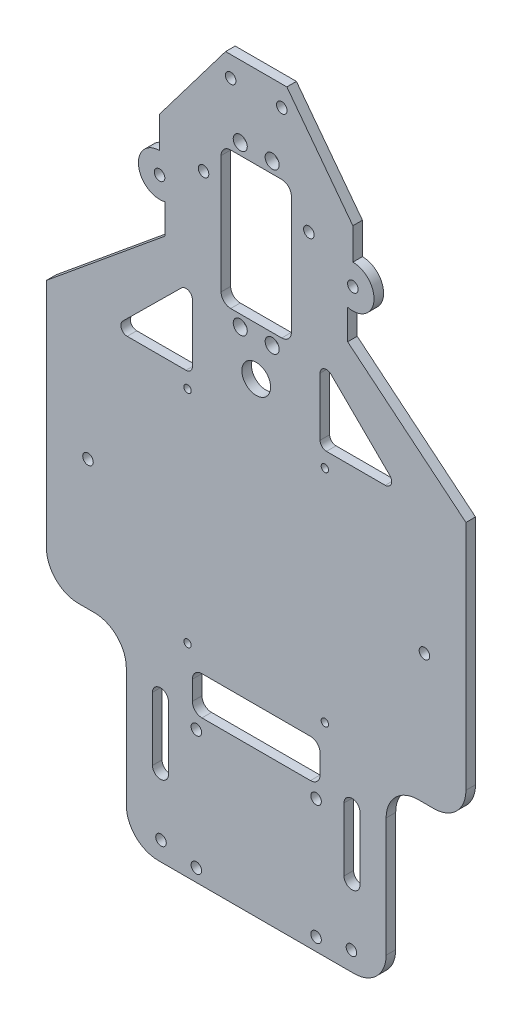
SolidWorks part; units mm, degrees
ref_plane "Front Plane" through (0, 0, 0) normal (0, 0, 1) x (1, 0, 0)
ref_plane "Top Plane" through (0, 0, 0) normal (0, 1, 0) x (1, 0, 0)
ref_plane "Right Plane" through (0, 0, 0) normal (1, 0, 0) x (0, 0, -1)
sketch "Sketch1" plane through (0, 0, 0) normal (0, 0, 1) x (1, 0, 0)
  line L0 (0, 88.6559) -> (0, -280.1214) construction
  line L6 (-65.69, -25.0893) -> (-65.69, -107.7412)
  line L7 (-65.69, -107.7412) -> (-40.69, -107.7412)
  line L8 (-40.69, -107.7412) -> (-40.69, -164.9822)
  line L9 (-40.69, -164.9822) -> (40.69, -164.9822)
  line L14 (65.69, -25.0893) -> (65.69, -107.7412)
  line L15 (65.69, -107.7412) -> (40.69, -107.7412)
  line L16 (40.69, -107.7412) -> (40.69, -164.9822)
  line L17 (-29.8217, -153.2205) -> (-29.8217, -163.4841) construction
  line L18 (-37.8742, -161.3701) -> (-20.3793, -161.3701) construction
  line L19 (-52.6928, -38.7906) -> (-52.6928, -94.6639) construction
  line L20 (-83.9092, -67.0943) -> (-28.9526, -67.0943) construction
  line L21 (52.6928, -38.7906) -> (52.6928, -94.6639) construction
  line L22 (83.9092, -67.0943) -> (28.9526, -67.0943) construction
  line L23 (37.8742, -161.3701) -> (20.3793, -161.3701) construction
  line L24 (29.8217, -153.2205) -> (29.8217, -163.4841) construction
  line L27 (-65.69, -25.0893) -> (-28.6418, 5.3966)
  line L28 (-30, -120.271) -> (-30, -140.086) construction
  line L29 (-11, 39.1077) -> (11, 39.1077)
  line L30 (-11, 39.1077) -> (-11, -3.8923)
  line L31 (-11, -3.8923) -> (11, -3.8923)
  line L32 (11, 39.1077) -> (11, -3.8923)
  line L33 (-11, 39.1077) -> (11, -3.8923) construction
  line L34 (-11, -3.8923) -> (11, 39.1077) construction
  line L35 (-20, -104.4501) -> (20, -104.4501)
  line L36 (-20, -104.4501) -> (-20, -116.4501)
  line L37 (-20, -116.4501) -> (20, -116.4501)
  line L38 (20, -104.4501) -> (20, -116.4501)
  line L39 (-20, -104.4501) -> (20, -116.4501) construction
  line L40 (-20, -116.4501) -> (20, -104.4501) construction
  line L43 (-27.5, -120.271) -> (-27.5, -140.086)
  line L44 (-32.5, -120.271) -> (-32.5, -140.086)
  line L45 (30, -120.271) -> (30, -140.086) construction
  line L46 (27.5, -120.271) -> (27.5, -140.086)
  line L47 (32.5, -120.271) -> (32.5, -140.086)
  line L48 (20, -2.6427) -> (20, -27.6411)
  line L49 (20, -27.6411) -> (45.282, -27.6411)
  line L50 (45.282, -27.6411) -> (20, -2.6427)
  line L51 (-20, -27.6411) -> (-45.282, -27.6411)
  line L52 (-20, -2.6427) -> (-20, -27.6411)
  line L53 (-45.282, -27.6411) -> (-20, -2.6427)
  line L54 (-28.6418, 5.3966) -> (-28.6418, 14.7716)
  line L55 (-30.2776, 27.8213) -> (-30.2776, 37.6956)
  line L56 (-30.2776, 37.6956) -> (-9.5976, 65.0178)
  line L57 (-9.5976, 65.0178) -> (9.5976, 65.0178)
  line L58 (65.69, -25.0893) -> (28.6418, 5.3966)
  line L59 (28.6418, 5.3966) -> (28.6418, 14.7716)
  line L60 (30.2776, 27.8213) -> (30.2776, 37.6956)
  line L61 (30.2776, 37.6956) -> (9.5976, 65.0178)
  line L62 (-5.5214, -18.9822) -> (5.7974, -18.9822) construction
  line L63 (-49.4927, 29.1077) -> (49.3693, 29.1077) construction
  line L64 (-16.5, 40.8846) -> (-16.5, 28.6939) construction
  line L65 (16.5, 40.8846) -> (16.5, 28.6939) construction
  line L66 (-43.1126, 58.6077) -> (47.2987, 58.6077) construction
  line L67 (-8, 55.9424) -> (-8, 45.929) construction
  line L68 (8, 55.9424) -> (8, 45.929) construction
  line L69 (-40.69, 17.6077) -> (39.8694, 17.6077) construction
  line L70 (-11.4384, 42.6077) -> (11.9873, 42.6077) construction
  line L71 (5, 45.2623) -> (5, 40.4022) construction
  line L72 (-5, 45.2623) -> (-5, 40.4022) construction
  line L73 (-11.4384, -7.3923) -> (11.9873, -7.3923) construction
  line L74 (-5, -10.0468) -> (-5, -5.1867) construction
  line L75 (5, -10.0468) -> (5, -5.1867) construction
  line L76 (-36.2555, -160.9822) -> (34.7157, -160.9822) construction
  line L77 (-23.9765, -142.2322) -> (17.7395, -142.2322) construction
  line L78 (-18.75, -157.7593) -> (-18.75, -163.4841) construction
  line L79 (18.75, -157.7593) -> (18.75, -163.4841) construction
  line L80 (-36.2555, -123.4822) -> (34.7157, -123.4822) construction
  line L81 (18.75, -126.7051) -> (18.75, -120.9804) construction
  line L82 (-18.75, -126.7051) -> (-18.75, -120.9804) construction
  line L83 (-87.3317, -66.9501) -> (108.5415, -66.9501) construction
  line L84 (13.0043, -101.4501) -> (41.7879, -101.4501) construction
  line L85 (21.5, -89.8072) -> (21.5, -113.3293) construction
  line L86 (-13.0043, -101.4501) -> (-41.7879, -101.4501) construction
  line L87 (-21.5, -89.8072) -> (-21.5, -113.3293) construction
  line L88 (13.0043, -32.4501) -> (41.7879, -32.4501) construction
  line L89 (21.5, -44.0929) -> (21.5, -20.5709) construction
  line L90 (-13.0043, -32.4501) -> (-41.7879, -32.4501) construction
  line L91 (-21.5, -44.0929) -> (-21.5, -20.5709) construction
  circle A2 centre (-30.2776, 21.1939) radius 1.65
  circle A3 centre (-29.8217, -158.9822) radius 1.65
  circle A5 centre (-52.6928, -67.0943) radius 1.65
  circle A6 centre (30.2776, 21.1939) radius 1.65
  circle A7 centre (52.6928, -67.0943) radius 1.65
  circle A8 centre (29.8217, -158.9822) radius 1.65
  arc A13 (-27.5, -120.271) -> (-32.5, -120.271) centre (-30, -120.271) ccw
  arc A14 (-32.5, -140.086) -> (-27.5, -140.086) centre (-30, -140.086) ccw
  arc A15 (27.5, -120.271) -> (32.5, -120.271) centre (30, -120.271) cw
  arc A16 (32.5, -140.086) -> (27.5, -140.086) centre (30, -140.086) cw
  arc A19 (-28.6418, 14.7716) -> (-30.2776, 27.8213) centre (-30.2776, 21.1939) cw
  arc A20 (28.6418, 14.7716) -> (30.2776, 27.8213) centre (30.2776, 21.1939) ccw
  circle A21 centre (0, -18.9822) radius 4.5
  circle A22 centre (-16.5, 29.1077) radius 1.65
  circle A23 centre (16.5, 29.1077) radius 1.65
  circle A24 centre (-8, 58.6077) radius 1.65
  circle A25 centre (8, 58.6077) radius 1.65
  circle A26 centre (5, 42.6077) radius 2.2
  circle A27 centre (-5, 42.6077) radius 2.2
  circle A28 centre (5, -7.3923) radius 2.2
  circle A29 centre (-5, -7.3923) radius 2.2
  circle A30 centre (-18.75, -160.9822) radius 1.65
  circle A31 centre (18.75, -160.9822) radius 1.65
  circle A32 centre (18.75, -123.4822) radius 1.65
  circle A33 centre (-18.75, -123.4822) radius 1.65
  circle A34 centre (21.5, -101.4501) radius 1.15
  circle A35 centre (-21.5, -101.4501) radius 1.15
  circle A36 centre (21.5, -32.4501) radius 1.15
  circle A37 centre (-21.5, -32.4501) radius 1.15
  point P20 (0, 65.0178)
  point P29 (0, -164.9822)
  point P54 (0, 65.0178)
  point P61 (0, 17.6077)
  point P66 (0, -110.4501)
  point P73 (-30, -130.1785)
  point P80 (30, -130.1785)
  dimension "D4" = 59.6434
  dimension "D11" = 10
  dimension "D12" = 230
  dimension "D13" = 19.5
  dimension "D14" = 88.2882
  dimension "D17" = 43
  dimension "D21" = 30
  dimension "D5" = 105.3856
  dimension "D24" = 5
  dimension "D26" = 48.5321
  dimension "D33" = 18.75
  dimension "D34" = 3.3
  dimension "D35" = 4.4
  dimension "D36" = 3.3
  dimension "D37" = 3.3
  dimension "D38" = 3.3
  dimension "D41" = 34.5
  dimension "D42" = 3.3
  dimension "D3" = 65.69
  dimension "D6" = 91.8879
  dimension "D7" = 6
  dimension "D8" = 9.8743
  dimension "D9" = 25
  dimension "D10" = 16.5
  dimension "D15" = 60.5551
  dimension "D16" = 146
  dimension "D18" = 22
  dimension "D19" = 12
  dimension "D20" = 40
  dimension "D22" = 63.2021
  dimension "D23" = 8
  dimension "D25" = 25
  dimension "D27" = 82.6519
  dimension "D28" = 57.241
  dimension "D29" = 113.1378
  dimension "D30" = 9.375
  dimension "D31" = 4
  dimension "D32" = 18.75
  dimension "D39" = 3
  dimension "D40" = 21.5
extrude "Boss-Extrude1" add sketch "Sketch1" along normal blind 3
fillet "Fillet2" radius 3 4 edges at (11, -3.8923, 1.5) (-11, -3.8923, 1.5) (11, 39.1077, 1.5) (-11, 39.1077, 1.5)
fillet "Fillet3" radius 2 6 edges at (45.282, -27.6411, 1.5) (20, -27.6411, 1.5) (20, -2.6427, 1.5) (-20, -27.6411, 1.5) (-45.282, -27.6411, 1.5) (-20, -2.6427, 1.5)
fillet "Fillet4" radius 10 6 edges at (40.69, -164.9822, 1.5) (-40.69, -164.9822, 1.5) (-40.69, -107.7412, 1.5) (-65.69, -107.7412, 1.5) (40.69, -107.7412, 1.5) (65.69, -107.7412, 1.5)
sketch "Sketch2" plane through (0, -104.4501, 0) normal (0, -1, 0) x (1, 0, 0)
  line L1 (-20, 3) -> (20, 3)
  line L2 (-20, 3) -> (-20, 0)
  line L3 (-20, 0) -> (20, 0)
  line L4 (20, 3) -> (20, 0)
extrude "Boss-Extrude2" add sketch "Sketch2" along normal blind 3
sketch "Sketch3" plane through (0, -116.4501, 0) normal (0, 1, 0) x (1, 0, 0)
  line L1 (-20, 0) -> (20, 0)
  line L2 (-20, 0) -> (-20, -3)
  line L3 (-20, -3) -> (20, -3)
  line L4 (20, 0) -> (20, -3)
extrude "Cut-Extrude1" cut sketch "Sketch3" against normal blind 3
fillet "Fillet5" radius 3 4 edges at (-20, -107.4501, 1.5) (20, -107.4501, 1.5) (20, -119.4501, 1.5) (-20, -119.4501, 1.5)
